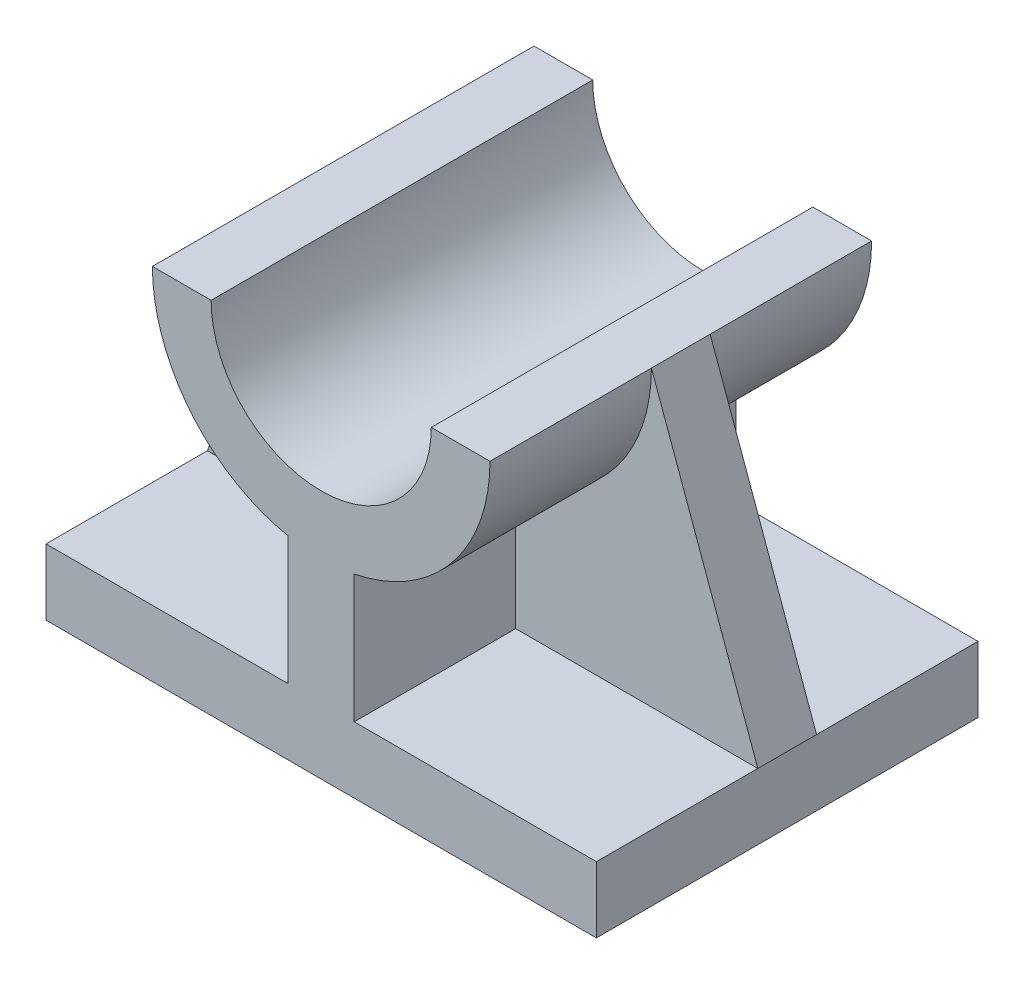
SolidWorks part; units mm, degrees
ref_plane "Front Plane" through (0, 0, 0) normal (0, 0, 1) x (1, 0, 0)
ref_plane "Top Plane" through (0, 0, 0) normal (0, 1, 0) x (1, 0, 0)
ref_plane "Right Plane" through (0, 0, 0) normal (1, 0, 0) x (0, 0, -1)
sketch "Sketch1" plane through (0, 0, 0) normal (0, 0, 1) x (1, 0, 0)
  line L0 (-23, 44.5) -> (-15, 44.5)
  line L1 (-37.5, 4.5) -> (-4.5, 4.5)
  line L2 (-37.5, 4.5) -> (-37.5, -4.5)
  line L3 (-37.5, -4.5) -> (37.5, -4.5)
  line L4 (37.5, 4.5) -> (37.5, -4.5)
  line L5 (-37.5, 4.5) -> (37.5, -4.5) construction
  line L6 (-37.5, -4.5) -> (37.5, 4.5) construction
  line L7 (15, 44.5) -> (23, 44.5)
  line L8 (-4.5, 4.5) -> (-4.5, 21.9445)
  line L9 (0, 0) -> (0, 44.5) construction
  line L10 (4.5, 4.5) -> (4.5, 21.9445)
  line L11 (4.5, 4.5) -> (37.5, 4.5)
  arc A1 (-15, 44.5) -> (15, 44.5) centre (0, 44.5) ccw
  arc A2 (-23, 44.5) -> (-4.5, 21.9445) centre (0, 44.5) ccw
  arc A3 (4.5, 21.9445) -> (23, 44.5) centre (0, 44.5) ccw
  point P0 (0, 0)
  dimension "D3" = 30
  dimension "D4" = 46
  dimension "D1" = 9
  dimension "D2" = 75
  dimension "D5" = 40
  dimension "D6" = 4.5
extrude "Boss-Extrude1" add sketch "Sketch1" along normal mid plane 52
sketch "Sketch2" plane through (0, 0, 0) normal (0, 0, 1) x (1, 0, 0)
  line L0 (23, 44.5) -> (37.5, 4.5)
rib "Rib11" sketch "Sketch2" sketch "Sketch2" thickness 8 extrusion direction parallel to sketch draft on no parameters "D1"=8
mirror "Mirror1" about plane through (0, 0, 0) normal (1, 0, 0) of "Rib11"
